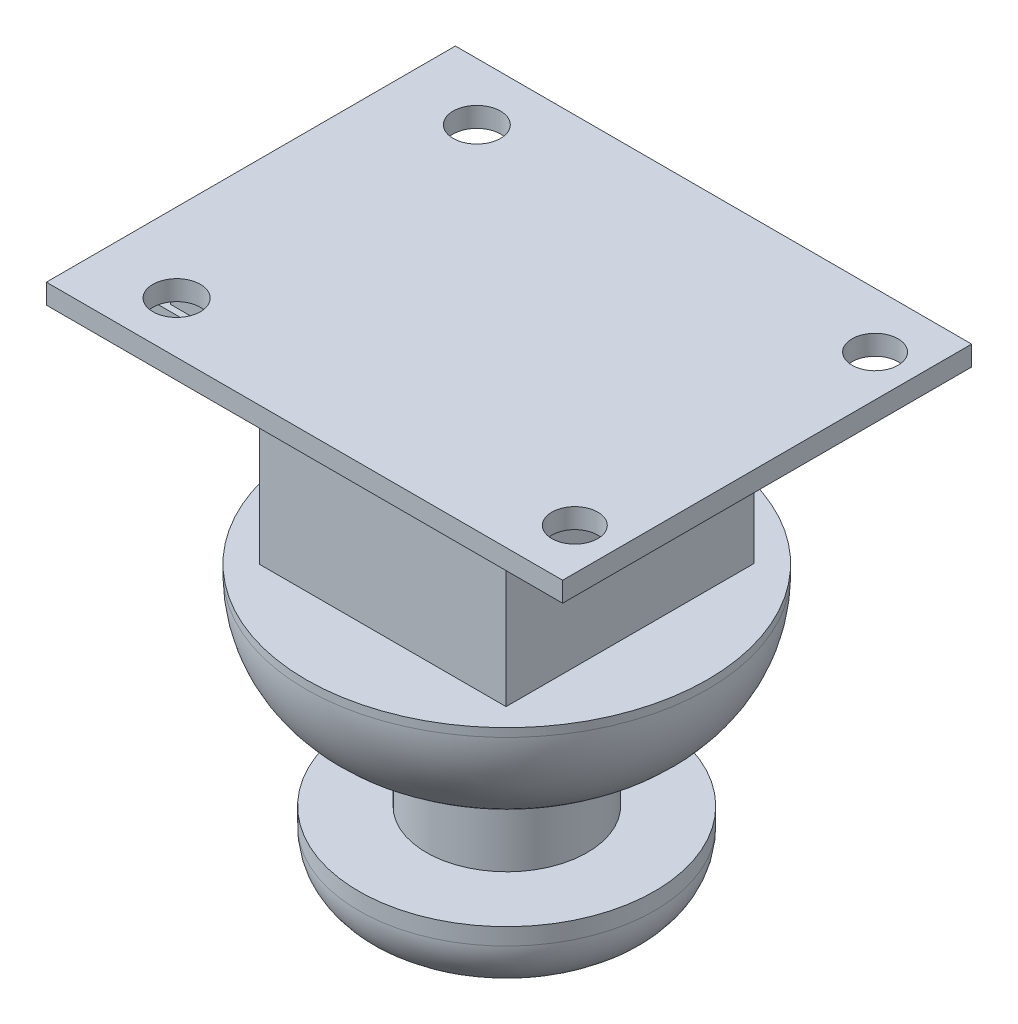
SolidWorks part; units mm, degrees
ref_plane "Спереди" through (0, 0, 0) normal (0, 0, 1) x (1, 0, 0)
ref_plane "Сверху" through (0, 0, 0) normal (0, 1, 0) x (1, 0, 0)
ref_plane "Справа" through (0, 0, 0) normal (1, 0, 0) x (0, 0, -1)
sketch "Эскиз1" plane through (0, 0, 0) normal (0, 1, 0) x (1, 0, 0)
  line L0 (33.7, 0) -> (30.9983, 0) construction
  line L1 (33.7, 26.7) -> (0, 26.7)
  line L2 (33.7, 26.7) -> (33.7, 0)
  line L3 (33.7, 0) -> (0, 0)
  line L4 (0, 26.7) -> (0, 0)
  line L5 (30.9983, 0) -> (30.9983, 3.4986) construction
  line L6 (30.9983, 3.4986) -> (33.7, 3.4986) construction
  line L7 (33.7, 26.7) -> (30.9983, 26.7) construction
  line L8 (30.9983, 26.7) -> (30.9983, 23.0985) construction
  line L9 (30.9983, 23.0985) -> (33.7, 23.0985) construction
  line L10 (0, 0) -> (5.1505, 0) construction
  line L11 (5.1505, 0) -> (5.1505, 3.3527) construction
  line L12 (5.1505, 3.3527) -> (0, 3.3527) construction
  line L13 (0, 26.7) -> (5.1505, 26.7) construction
  line L14 (5.1505, 26.7) -> (5.1505, 22.95) construction
  line L15 (5.1505, 22.95) -> (0, 22.95) construction
  circle A0 centre (30.9983, 3.4986) radius 1.5002
  circle A1 centre (30.9983, 23.0985) radius 1.5
  circle A2 centre (5.1505, 3.3527) radius 1.5523
  circle A3 centre (5.1505, 22.95) radius 1.5465
  point P12 (30.9983, 21.5985)
  point P13 (30.9983, 4.9988)
  point P14 (30.9983, 1.9985)
  point P15 (30.9983, 24.5985)
  point P16 (32.4984, 3.4986)
  point P25 (5.1505, 21.4035)
  point P26 (5.1505, 24.4965)
extrude "Бобышка-Вытянуть1" add sketch "Эскиз1" along normal blind 1.3
sketch "Эскиз2" plane through (0, 0, 0) normal (0, -1, 0) x (1, 0, 0)
  line L0 (0, 0) -> (0, -6.6956) construction
  line L1 (0, -26.7) -> (0, 0) construction
  line L2 (0, -6.6956) -> (1.3986, -6.6956) construction
  line L4 (1.3986, -6.6956) -> (3.9964, -6.6956)
  line L5 (1.3986, -6.6956) -> (1.3986, -19.292)
  line L6 (1.3986, -19.292) -> (3.9964, -19.292)
  line L7 (3.9964, -6.6956) -> (3.9964, -19.292)
extrude "Бобышка-Вытянуть3" add sketch "Эскиз2" along normal blind 2.6
sketch "Эскиз3" plane through (0, -2.6, 0) normal (0, -1, 0) x (1, 0, 0)
  line L0 (1.3986, -19.292) -> (1.3986, -18.491) construction
  line L1 (1.3986, -6.6956) -> (1.3986, -19.292) construction
  line L2 (1.3986, -18.491) -> (2.2964, -18.491) construction
  line L3 (3.0979, -18.491) -> (3.9964, -18.491) construction
  line L4 (2.2964, -18.491) -> (3.0979, -18.491)
  line L5 (2.2964, -18.491) -> (2.2964, -17.6906)
  line L6 (2.2964, -17.6906) -> (3.0979, -17.6906)
  line L7 (3.0979, -18.491) -> (3.0979, -17.6906)
  line L8 (3.9964, -19.292) -> (3.9964, -6.6956) construction
  line L9 (2.2964, -17.6906) -> (2.2964, -16.0942) construction
  line L10 (2.2964, -15.2921) -> (2.2964, -13.4902) construction
  line L11 (2.2964, -16.0942) -> (3.0979, -16.0942)
  line L12 (2.2964, -16.0942) -> (2.2964, -15.2921)
  line L13 (2.2964, -15.2921) -> (3.0979, -15.2921)
  line L14 (3.0979, -16.0942) -> (3.0979, -15.2921)
  line L15 (2.2964, -12.6917) -> (2.2964, -11.0905) construction
  line L16 (2.2964, -13.4902) -> (3.0979, -13.4902)
  line L17 (2.2964, -13.4902) -> (2.2964, -12.6917)
  line L18 (2.2964, -12.6917) -> (3.0979, -12.6917)
  line L19 (3.0979, -13.4902) -> (3.0979, -12.6917)
  line L20 (2.2964, -10.2875) -> (2.2964, -8.4842) construction
  line L21 (2.2964, -11.0905) -> (3.0979, -11.0905)
  line L22 (2.2964, -11.0905) -> (2.2964, -10.2875)
  line L23 (2.2964, -10.2875) -> (3.0979, -10.2875)
  line L24 (3.0979, -11.0905) -> (3.0979, -10.2875)
  line L25 (2.2964, -7.6799) -> (2.2964, -6.6956) construction
  line L26 (2.2964, -8.4842) -> (3.0979, -8.4842)
  line L27 (2.2964, -8.4842) -> (2.2964, -7.6799)
  line L28 (2.2964, -7.6799) -> (3.0979, -7.6799)
  line L29 (3.0979, -8.4842) -> (3.0979, -7.6799)
  line L30 (3.9964, -6.6956) -> (1.3986, -6.6956) construction
sketch "Эскиз4" plane through (0, 0, 0) normal (0, 0, 1) x (1, 0, 0)
  line L0 (2.6971, -2.6) -> (2.6971, -3.4)
  line L1 (1.6971, -4.4) -> (-4.903, -4.4)
  line L2 (2.2964, -2.6) -> (3.0979, -2.6) construction
  arc A0 (2.6971, -3.4) -> (1.6971, -4.4) centre (1.6971, -3.4) cw
  dimension "D1" = 1
ref_plane "Плоскость3" through (2.6971, -2.6, 0) normal (0, -1, 0) x (-1, 0, 0)
sweep "По траектории3" add profiles "Эскиз3" path "Эскиз4"
sketch "Эскиз6" plane through (0, 0, 0) normal (0, -1, 0) x (1, 0, 0)
  line L0 (0, -26.7) -> (9.2005, -26.7) construction
  line L1 (33.7, -26.7) -> (0, -26.7) construction
  line L2 (9.2005, -26.7) -> (9.2005, -20.905) construction
  line L3 (9.2005, -20.905) -> (25.3022, -20.905) construction
  line L4 (25.3022, -20.905) -> (25.3022, -4.7062) construction
  line L6 (25.3022, -20.905) -> (9.2005, -20.905)
  line L7 (25.3022, -20.905) -> (25.3022, -4.7062)
  line L8 (25.3022, -4.7062) -> (9.2005, -4.7062)
  line L9 (9.2005, -20.905) -> (9.2005, -4.7062)
extrude "Бобышка-Вытянуть4" add sketch "Эскиз6" along normal blind 12.4
sketch "Эскиз7" plane through (0, -12.4, 0) normal (0, -1, 0) x (1, 0, 0)
  line L0 (9.2005, -4.7062) -> (25.3022, -20.905) construction
  line L1 (25.3022, -20.905) -> (25.3022, -4.7062) construction
  line L2 (25.3022, -4.7062) -> (17.2514, -12.8056) construction
  circle A0 centre (17.2514, -12.8056) radius 13.1019
extrude "Бобышка-Вытянуть5" add sketch "Эскиз7" along normal blind 8.4
fillet "Скругление1" radius 7.85 1 edges at (17.2514, -20.8, -25.9075)
sketch "Эскиз9" plane through (0, -20.8, 0) normal (0, -1, 0) x (1, 0, 0)
  line L0 (15.3232, -7.9204) -> (19.1796, -17.6908) construction
  circle A0 centre (17.2514, -12.8056) radius 5.2519 construction
  arc A1 (19.1796, -17.6908) -> (22.1365, -10.8774) centre (17.2514, -12.8056) ccw construction
  circle A2 centre (17.2514, -12.8056) radius 5.2519
extrude "Бобышка-Вытянуть6" add sketch "Эскиз9" along normal blind 5.3
sketch "Эскиз12" plane through (0, -26.1, 0) normal (0, -1, 0) x (1, 0, 0)
  line L0 (15.4657, -7.8666) -> (19.007, -17.7554) construction
  circle A0 centre (17.2514, -12.8056) radius 5.2519 construction
  circle A1 centre (17.2363, -12.811) radius 9.6512
extrude "Бобышка-Вытянуть8" add sketch "Эскиз12" along normal blind 4.6
fillet "Скругление2" radius 3.5 1 edges at (17.2363, -30.7, -22.4621)
